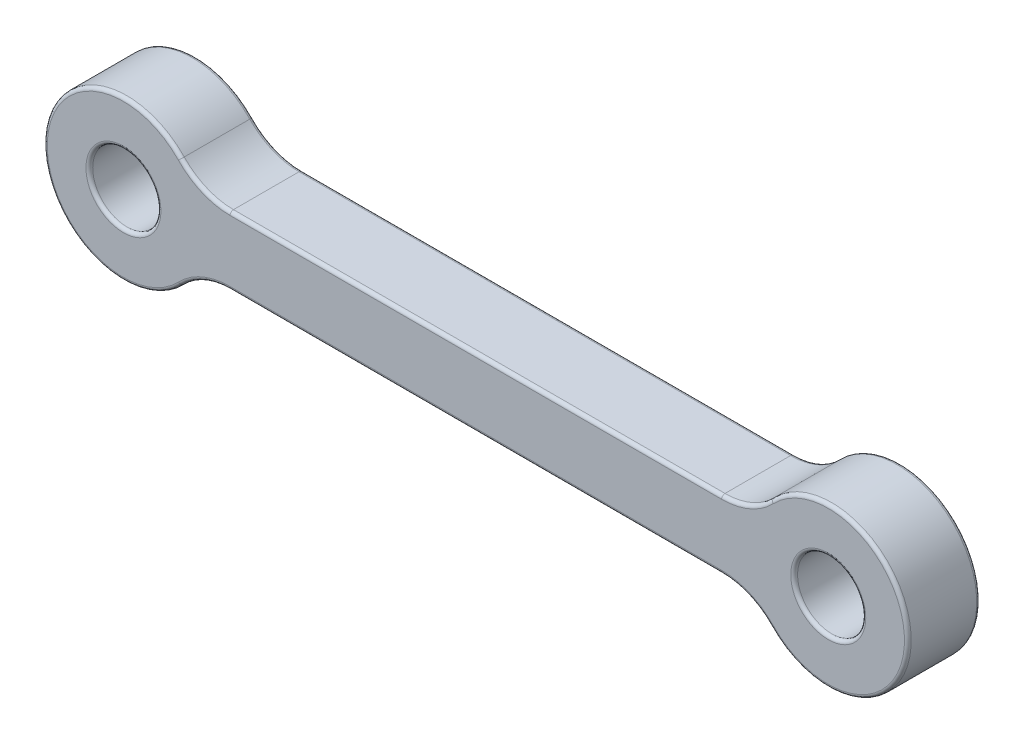
SolidWorks part; units mm, degrees
ref_plane "Front Plane" through (0, 0, 0) normal (0, 0, 1) x (1, 0, 0)
ref_plane "Top Plane" through (0, 0, 0) normal (0, 1, 0) x (1, 0, 0)
ref_plane "Right Plane" through (0, 0, 0) normal (1, 0, 0) x (0, 0, -1)
sketch "Sketch1" plane through (0, 0, 0) normal (0, 0, 1) x (1, 0, 0)
  line L0 (0, 0) -> (31, 0) construction
  line L1 (0, 3.5) -> (31, 3.5) construction
  line L2 (0, -3.5) -> (31, -3.5) construction
  line L3 (15.5, 0) -> (15.5, -3.5) construction
  line L5 (27.8377, 1.5) -> (3.1623, 1.5)
  line L6 (27.8377, 1.5) -> (27.8377, -1.5) construction
  line L7 (27.8377, -1.5) -> (3.1623, -1.5)
  line L8 (3.1623, 1.5) -> (3.1623, -1.5) construction
  line L9 (27.8377, 1.5) -> (3.1623, -1.5) construction
  line L10 (27.8377, -1.5) -> (3.1623, 1.5) construction
  arc A0 (0, 3.5) -> (0, -3.5) centre (0, 0) ccw construction
  arc A1 (31, -3.5) -> (31, 3.5) centre (31, 0) ccw construction
  circle A2 centre (0, 0) radius 1.5
  circle A3 centre (0, 0) radius 3.5
  circle A4 centre (31, 0) radius 1.5
  circle A5 centre (31, 0) radius 3.5
  point P3 (15.5, 0)
  dimension "D3" = 3
  dimension "D1" = 31
  dimension "D2" = 7
  dimension "D4" = 3
extrude "Boss-Extrude1" add sketch "Sketch1" along normal blind 3.18 contours A3 A2 | L7 A5 L5 A3 | A5 A4
fillet "Fillet1" radius 3 4 edges at (27.8377, 1.5, 1.59) (3.1623, 1.5, 1.59) (27.8377, -1.5, 1.59) (3.1623, -1.5, 1.59)
fillet "Fillet2" radius 0.15 20 edges at (32.5, 0, 3.18) (32.5, 0, 0) (1.5, 0, 3.18) (1.5, 0, 0) (27.4863, -1.7404, 3.18) (27.4863, -1.7404, 0) (15.5, -1.5, 0) (15.5, -1.5, 3.18) (3.5137, -1.7404, 3.18) (3.5137, -1.7404, 0) (-3.5, 0, 3.18) (-3.5, 0, 0) (3.5137, 1.7404, 3.18) (3.5137, 1.7404, 0) (15.5, 1.5, 3.18) (15.5, 1.5, 0) (27.4863, 1.7404, 3.18) (27.4863, 1.7404, 0) (34.5, 0, 0) (34.5, 0, 3.18)
